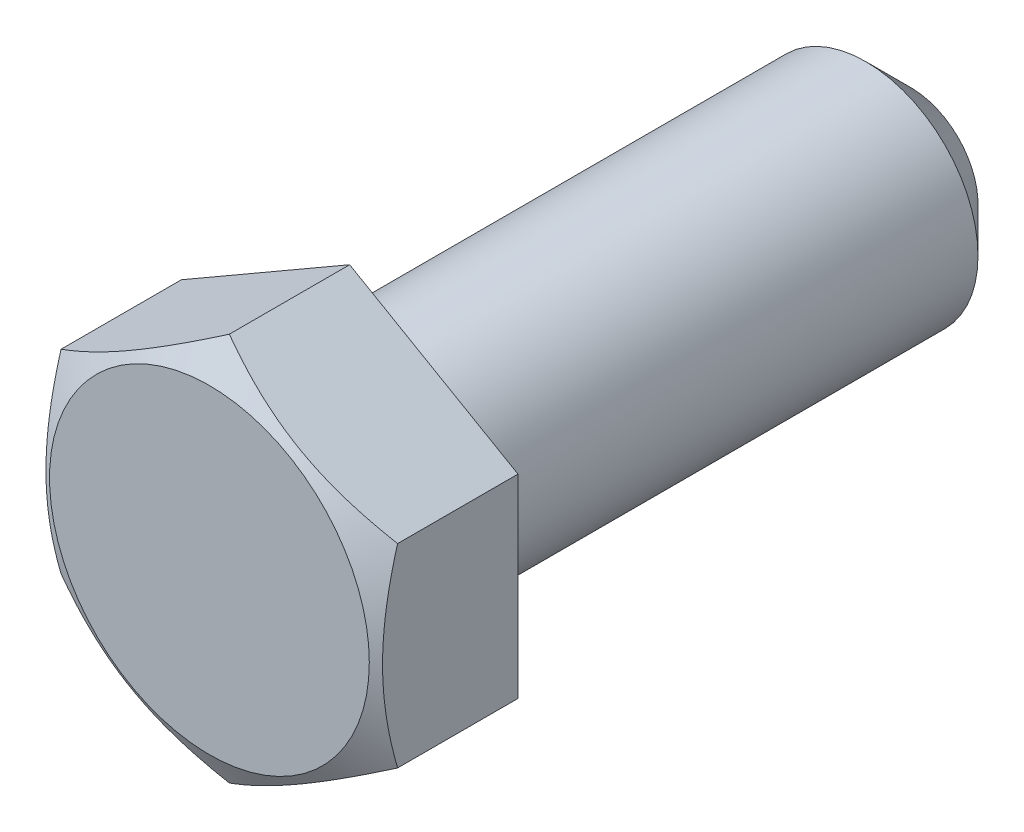
SolidWorks part; units mm, degrees
ref_plane "Плоскость1" through (0, 0, 0) normal (0, 0, 1) x (1, 0, 0)
ref_plane "Плоскость2" through (0, 0, 0) normal (0, 1, 0) x (1, 0, 0)
ref_plane "Плоскость3" through (0, 0, 0) normal (1, 0, 0) x (0, 0, -1)
sketch "Шестигранник" plane through (0, 0, 0) normal (0, 0, 1) x (1, 0, 0)
  line L1 (0, -6.9282) -> (6, -3.4641)
  line L2 (6, -3.4641) -> (6, 3.4641)
  line L3 (6, 3.4641) -> (0, 6.9282)
  line L4 (0, 6.9282) -> (-6, 3.4641)
  line L5 (-6, 3.4641) -> (-6, -3.4641)
  line L6 (-6, -3.4641) -> (0, -6.9282)
  circle A0 centre (0, 0) radius 6 construction
  dimension "D1" = 12
extrude "Головка" add sketch "Шестигранник" along normal blind 5
sketch "D" plane through (0, 0, 5) normal (0, 0, 1) x (1, 0, 0)
  circle A0 centre (0, 0) radius 5.7
  dimension "D1" = 11.4
extrude "Фаска головки" cut sketch "D" against normal blind 10 draft 60 flip side to cut
sketch "Диаметр" plane through (0, 0, 0) normal (0, 0, -1) x (-1, 0, 0)
  circle A0 centre (0, 0) radius 4
  dimension "D1" = 8
extrude "Стержень" add sketch "Диаметр" along normal blind 20
cosmetic thread "Резьба"
chamfer "Фаска резьбы" distance 1.6 angle 45 1 edges at (-4, 0, -20)
equation "\"D1@D\" = 0.95 * \"D1@Шестигранник\""
